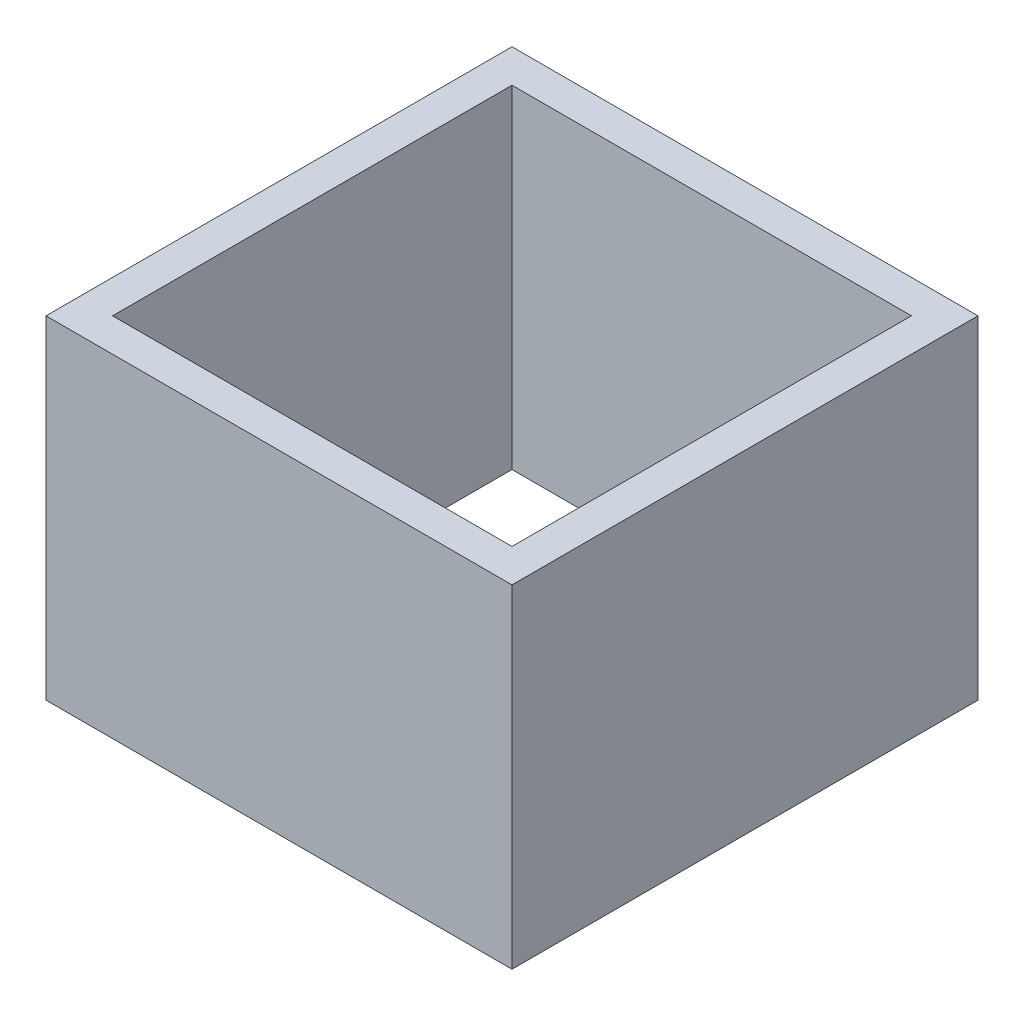
SolidWorks part; units mm, degrees
material "Acrylic (Medium-high impact)"
ref_plane "Front Plane" through (0, 0, 0) normal (0, 0, 1) x (1, 0, 0)
ref_plane "Top Plane" through (0, 0, 0) normal (0, 1, 0) x (1, 0, 0)
ref_plane "Right Plane" through (0, 0, 0) normal (1, 0, 0) x (0, 0, -1)
sketch "Sketch1" plane through (0, 0, 0) normal (0, 1, 0) x (1, 0, 0)
  line L1 (-44.45, 44.45) -> (44.45, 44.45)
  line L2 (-44.45, 44.45) -> (-44.45, -44.45)
  line L3 (-44.45, -44.45) -> (44.45, -44.45)
  line L4 (44.45, 44.45) -> (44.45, -44.45)
  line L5 (-44.45, 44.45) -> (44.45, -44.45) construction
  line L6 (-44.45, -44.45) -> (44.45, 44.45) construction
  point P0 (0, 0)
  dimension "D1" = 88.9
  dimension "D2" = 88.9
extrude "Boss-Extrude1" add sketch "Sketch1" along normal blind 63.5
sketch "Sketch2" plane through (0, 0, 0) normal (0, 1, 0) x (1, 0, 0)
  line L1 (-38.1, 38.1) -> (38.1, 38.1)
  line L2 (-38.1, 38.1) -> (-38.1, -38.1)
  line L3 (-38.1, -38.1) -> (38.1, -38.1)
  line L4 (38.1, 38.1) -> (38.1, -38.1)
  line L5 (-38.1, 38.1) -> (38.1, -38.1) construction
  line L6 (-38.1, -38.1) -> (38.1, 38.1) construction
  point P0 (0, 0)
  dimension "D1" = 76.2
  dimension "D2" = 76.2
extrude "Cut-Extrude1" cut sketch "Sketch2" along normal through all
